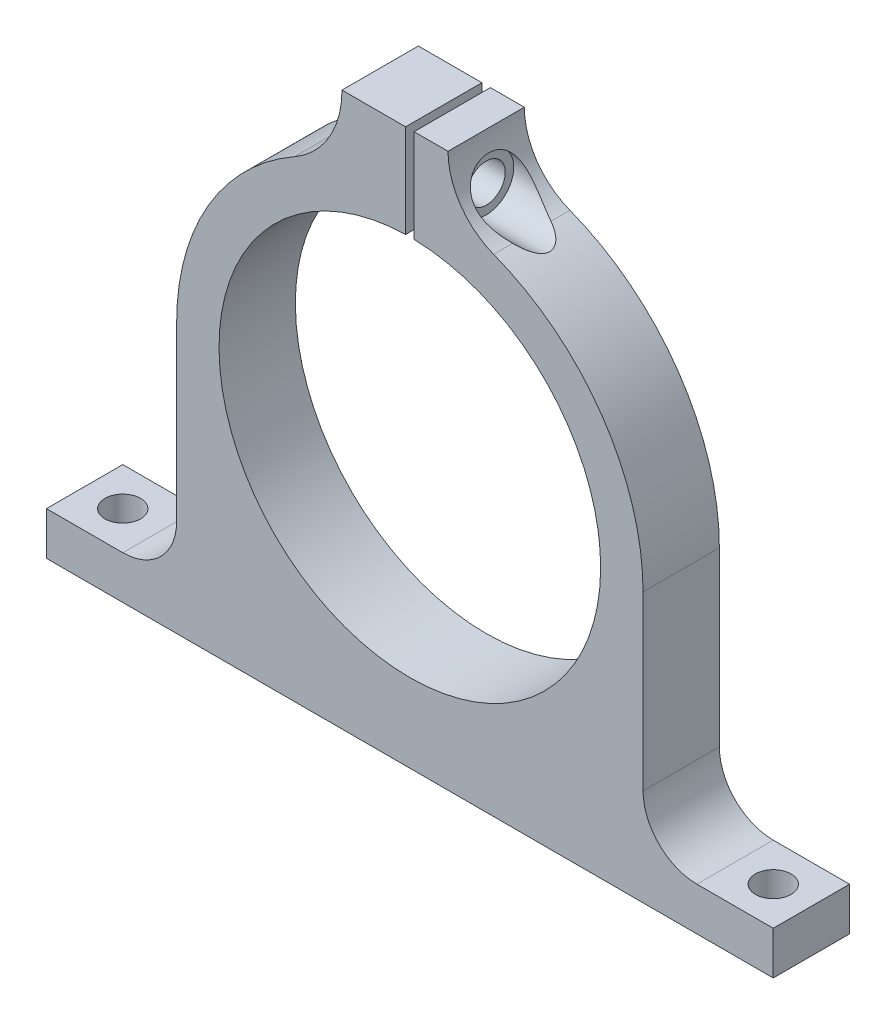
SolidWorks part; units mm, degrees
ref_plane "Front Plane" through (0, 0, 0) normal (0, 0, 1) x (1, 0, 0)
ref_plane "Top Plane" through (0, 0, 0) normal (0, 1, 0) x (1, 0, 0)
ref_plane "Right Plane" through (0, 0, 0) normal (1, 0, 0) x (0, 0, -1)
sketch "Sketch1" plane through (0, 0, 0) normal (0, 0, 1) x (1, 0, 0)
  line L0 (0, 0) -> (0, 55) construction
  line L1 (0, 0) -> (85.7, 0) construction
  line L2 (0, 0) -> (-85.7, 0) construction
  line L3 (85.7, -53.34) -> (85.7, -63.5)
  line L4 (85.7, -63.5) -> (-85.7, -63.5)
  line L5 (-85.7, -63.5) -> (-85.7, -53.34)
  line L6 (0, 55) -> (0, 67) construction
  line L7 (0, 67) -> (1, 67) construction
  line L8 (1, 67) -> (1, 44.9889)
  line L9 (1, 67) -> (9, 67)
  line L10 (-45, 0) -> (-55, 0) construction
  line L11 (0, 67) -> (-1, 67) construction
  line L12 (-1, 67) -> (-1, 44.9889)
  line L13 (-1, 67) -> (-16, 67)
  line L14 (-55, 0) -> (-55, -40.64)
  line L15 (-67.7, -53.34) -> (-85.7, -53.34)
  line L16 (55, 0) -> (55, -40.64)
  line L17 (67.7, -53.34) -> (85.7, -53.34)
  arc A0 (-1, 44.9889) -> (1, 44.9889) centre (0, 0) ccw
  arc A1 (55, 0) -> (19.76, 51.3278) centre (0, 0) ccw
  arc A2 (-27.1614, 47.8253) -> (-55, 0) centre (0, 0) ccw
  arc A3 (9, 67) -> (19.76, 51.3278) centre (25.7935, 67) ccw
  arc A4 (55, -40.64) -> (67.7, -53.34) centre (67.7, -40.64) ccw
  arc A5 (-55, -40.64) -> (-67.7, -53.34) centre (-67.7, -40.64) cw
  arc A6 (-27.1614, 47.8253) -> (-16, 67) centre (-38.0513, 67) ccw
  dimension "D1" = 90
  dimension "D3" = 12.7
  dimension "D4" = 18
  dimension "D2" = 10
  dimension "D5" = 10.16
  dimension "D6" = 12
  dimension "D7" = 1
  dimension "D8" = 8
  dimension "D9" = 1
  dimension "D10" = 15
  dimension "D11" = 63.5
extrude "main body" add sketch "Sketch1" along normal blind 18
sketch "Sketch7" plane through (1, 0, 0) normal (-1, 0, 0) x (0, 0, 1)
  line L0 (9, 44.9889) -> (9, 67) construction
  line L1 (18, 44.9889) -> (0, 44.9889) construction
  line L2 (18, 67) -> (0, 67) construction
  circle A0 centre (9, 55.9944) radius 3.5
  dimension "D1" = 7
ref_plane "Plane3" through (9, 0, 0) normal (-1, 0, 0) x (0, 0, 1)
sketch "Sketch10" plane through (9, 0, 0) normal (-1, 0, 0) x (0, 0, 1)
  circle A0 centre (9, 55.9944) radius 6.5
  point P3 (0, 0)
  point P4 (9.5625, 55.618)
  point P5 (9, 55.9944)
  dimension "D1" = 13
extrude "head counterbore" cut sketch "Sketch10" against normal blind 18
sketch "to table bolt locations" plane through (0, -53.34, 0) normal (0, 1, 0) x (1, 0, 0)
  line L0 (-76.7, 0) -> (-76.7, -18) construction
  line L1 (-67.7, 0) -> (-85.7, 0) construction
  line L2 (-67.7, -18) -> (-85.7, -18) construction
  line L3 (76.7, 0) -> (76.7, -18) construction
  line L4 (85.7, 0) -> (67.7, 0) construction
  line L5 (85.7, -18) -> (67.7, -18) construction
  circle A0 centre (-76.7, -9) radius 4.25
  circle A1 centre (76.7, -9) radius 4.25
  dimension "D1" = 8.5
sketch "Sketch12" plane through (9, 0, 0) normal (-1, 0, 0) x (0, 0, 1)
  line L0 (9, 44.9889) -> (9, 67) construction
  line L1 (18, 44.9889) -> (0, 44.9889) construction
  line L2 (18, 67) -> (0, 67) construction
  circle A0 centre (9, 55.9944) radius 4.25
  point P9 (9, 55.9944)
  dimension "D1" = 8.5
hole_wizard "to table M8 Clearance Hole1" positions "Sketch13" profile "Sketch14" hole size "M8" standard "ANSI Metric" end condition through all
sketch "Sketch13" plane through (0, -53.34, 0) normal (0, 1, 0) x (1, 0, 0)
  point P0 (-76.7, -9)
  point P3 (76.7, -9)
sketch "Sketch14" plane through (-76.7, -53.34, 9) normal (1, 0, 0) x (0, 0, 1)
  line L0 (0, 0) -> (0, 10.16)
  line L1 (0, 10.16) -> (4.2, 10.16)
  line L2 (4.2, 10.16) -> (4.2, 0)
  line L5 (4.2, 0) -> (0, 0)
  line L11 (0, -6.35) -> (0, 107.95) construction
  dimension "Thru Hole Dia." = 8.4
  dimension "Thru Hole Depth" = 10.16
sketch "Sketch15" plane through (-1, 0, 0) normal (1, 0, 0) x (0, 0, -1)
  circle A0 centre (-9, 55.9944) radius 7.9364
hole_wizard "M8x1.25 Tapped Hole1" positions "Sketch18" profile "Sketch19" tap size "M8x1.25" standard "ANSI Metric"
sketch "Sketch18" plane through (-1, 0, 0) normal (1, 0, 0) x (0, 0, -1)
  point P0 (-9, 55.9944)
sketch "Sketch19" plane through (-1, 55.9944, 9) normal (0, 1, 0) x (0, 0, -1)
  line L0 (0, 0) -> (0, 84.7)
  line L1 (0, 84.7) -> (3.4, 84.7)
  line L2 (3.4, 84.7) -> (3.4, 0)
  line L5 (3.4, 0) -> (0, 0)
  line L11 (0, -6.35) -> (0, 107.95) construction
  dimension "Thru Tap Drill Dia." = 6.8
  dimension "Thru Tap Drill Depth" = 84.7
cosmetic thread "Hole Thread1" parameters "D2"=8
hole_wizard "M8 Clearance Hole2" positions "Sketch20" profile "Sketch22" hole size "M8" standard "ANSI Metric"
sketch "Sketch20" plane through (9, 0, 0) normal (-1, 0, 0) x (0, 0, 1)
  point P0 (9, 55.9944)
sketch "Sketch22" plane through (9, 55.9944, 9) normal (0, 1, 0) x (0, 0, -1)
  line L0 (0, 0) -> (0, 10.7029)
  line L1 (0, 10.7029) -> (4.5, 7.999)
  line L2 (4.5, 7.999) -> (4.5, 0)
  line L5 (4.5, 0) -> (0, 0)
  line L10 (0, 10.7029) -> (-4.5, 7.999) construction
  line L11 (0, -6.35) -> (0, 107.95) construction
  dimension "Hole Dia." = 9
  dimension "Hole Depth" = 7.999
  dimension "Drill Angle" = 118
